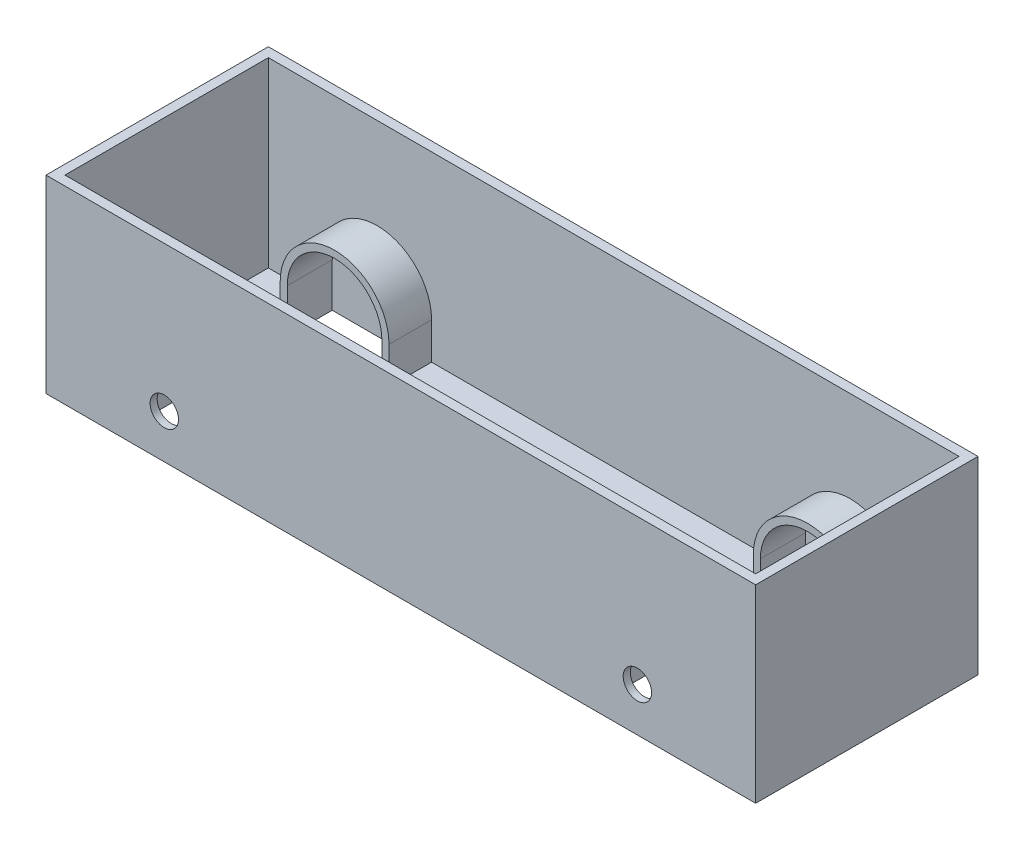
SolidWorks part; units mm, degrees
material "Aleación 1060"
ref_plane "Alzado" through (0, 0, 0) normal (0, 0, 1) x (1, 0, 0)
ref_plane "Planta" through (0, 0, 0) normal (0, 1, 0) x (1, 0, 0)
ref_plane "Vista lateral" through (0, 0, 0) normal (1, 0, 0) x (0, 0, -1)
sketch "Croquis1" plane through (0, 0, 0) normal (0, 0, 1) x (1, 0, 0)
  line L0 (0, 0) -> (50000, 0) construction
  line L1 (-120, -974.2204) -> (-120, 49025.7796) construction
  line L2 (-80, -974.2204) -> (-80, 49025.7796) construction
  line L3 (80, -1000) -> (80, 49000) construction
  line L4 (120, -1000) -> (120, 49000) construction
  line L5 (-150, 0) -> (-120, 0)
  line L6 (-80, 18.5) -> (-80, 0)
  line L7 (80, 0) -> (80, 18.5)
  line L8 (120, 18.5) -> (120, 0)
  line L9 (120, 0) -> (150, 0)
  line L10 (-80, 0) -> (80, 0)
  line L11 (-120, 18.5) -> (-120, 0)
  line L12 (-150, 3) -> (-123, 3)
  line L13 (-123, 18.5) -> (-123, 3)
  line L14 (-77, 18.5) -> (-77, 3)
  line L15 (-77, 3) -> (77, 3)
  line L16 (77, 3) -> (77, 18.5)
  line L17 (123, 18.5) -> (123, 3)
  line L18 (123, 3) -> (150, 3)
  line L19 (-150, 0) -> (-150, 3)
  line L20 (150, 0) -> (150, 3)
  circle A0 centre (-100, 18.5) radius 18.5 construction
  circle A1 centre (100, 18.5) radius 18.5 construction
  arc A2 (-80, 18.5) -> (-120, 18.5) centre (-100, 18.5) ccw
  arc A3 (120, 18.5) -> (80, 18.5) centre (100, 18.5) ccw
  arc A4 (-77, 18.5) -> (-123, 18.5) centre (-100, 18.5) ccw
  arc A5 (123, 18.5) -> (77, 18.5) centre (100, 18.5) ccw
  point P31 (0, 0)
  dimension "D2" = 37
  dimension "D3" = 40
  dimension "D1" = 200
  dimension "D4" = 300
  dimension "D5" = 3
extrude "Saliente-Extruir1" add sketch "Croquis1" along normal mid plane 94
sketch "Croquis2" plane through (123, 0, 0) normal (1, 0, 0) x (0, 0, -1)
  line L0 (-47, 3) -> (47, 3) construction
  line L1 (-25, 3) -> (25, 3)
  line L2 (-25, 3) -> (-25, 41.5)
  line L3 (-25, 41.5) -> (25, 41.5)
  line L4 (25, 3) -> (25, 41.5)
  line L5 (-47, 41.5) -> (-25, 41.5) construction
  line L6 (25, 41.5) -> (47, 41.5) construction
  dimension "D1" = 50
extrude "Cortar-Extruir1" cut sketch "Croquis2" against normal through all
sketch "Croquis3" plane through (0, 0, 47) normal (0, 0, 1) x (1, 0, 0)
  line L0 (120, 18.5) -> (120, 0) construction
  line L1 (80, 0) -> (80, 18.5) construction
  line L2 (-120, 0) -> (-120, 18.5) construction
  line L3 (-80, 18.5) -> (-80, 0) construction
  line L4 (120, 18.5) -> (120, 0)
  line L5 (80, 0) -> (80, 18.5)
  line L6 (-120, 0) -> (-120, 18.5)
  line L7 (-80, 18.5) -> (-80, 0)
  line L8 (-120, 0) -> (-80, 0)
  line L9 (80, 0) -> (120, 0)
  arc A0 (120, 18.5) -> (80, 18.5) centre (100, 18.5) ccw construction
  arc A1 (-80, 18.5) -> (-120, 18.5) centre (-100, 18.5) ccw construction
  arc A2 (120, 18.5) -> (80, 18.5) centre (100, 18.5) ccw
  arc A3 (-80, 18.5) -> (-120, 18.5) centre (-100, 18.5) ccw
extrude "Saliente-Extruir2" add sketch "Croquis3" against normal blind 3
mirror "Simetría1" about plane through (0, 0, 0) normal (0, 0, 1) of "Saliente-Extruir2"
sketch "Croquis4" plane through (0, 0, 47) normal (0, 0, 1) x (1, 0, 0)
  line L0 (150, 3) -> (150, 80)
  line L1 (150, 80) -> (-150, 80)
  line L2 (-150, 80) -> (-150, 3)
  line L10 (-150, 0) -> (150, 0)
  line L11 (150, 0) -> (150, 3)
  line L12 (150, 3) -> (123, 3)
  line L13 (123, 3) -> (123, 18.5)
  line L14 (77, 18.5) -> (77, 3)
  line L15 (77, 3) -> (-77, 3)
  line L16 (-77, 3) -> (-77, 18.5)
  line L17 (-123, 18.5) -> (-123, 3)
  line L18 (-123, 3) -> (-150, 3)
  line L19 (-150, 3) -> (-150, 0)
  line L20 (-150, 0) -> (150, 0)
  line L21 (150, 0) -> (150, 3)
  line L22 (150, 3) -> (123, 3)
  line L23 (123, 3) -> (123, 18.5)
  line L24 (77, 18.5) -> (77, 3)
  line L25 (77, 3) -> (-77, 3)
  line L26 (-77, 3) -> (-77, 18.5)
  line L27 (-123, 18.5) -> (-123, 3)
  line L28 (-123, 3) -> (-150, 3)
  line L29 (-150, 3) -> (-150, 0)
  arc A2 (123, 18.5) -> (77, 18.5) centre (100, 18.5) ccw
  arc A3 (-77, 18.5) -> (-123, 18.5) centre (-100, 18.5) ccw
  arc A4 (123, 18.5) -> (77, 18.5) centre (100, 18.5) ccw
  arc A5 (-77, 18.5) -> (-123, 18.5) centre (-100, 18.5) ccw
  line M16 (150, 3) -> (123, 3)
  line M17 (123, 3) -> (123, 18.5)
  arc M18 (123, 18.5) -> (77, 18.5) centre (100, 18.5) ccw
  line M19 (77, 18.5) -> (77, 3)
  line M20 (77, 3) -> (-77, 3)
  line M21 (-77, 3) -> (-77, 18.5)
  arc M22 (-77, 18.5) -> (-123, 18.5) centre (-100, 18.5) ccw
  line M23 (-123, 18.5) -> (-123, 3)
  line M24 (-123, 3) -> (-150, 3)
  dimension "D2" = 80
  dimension "D1" = 0
extrude "Saliente-Extruir3" add sketch "Croquis4" against normal blind 4 contours L1 L2 L0 M24 M23 M22 M21 M20 M19 M18 M17 M16
sketch "Croquis5" plane through (0, 0, -47) normal (0, 0, -1) x (-1, 0, 0)
  line L0 (123, 3) -> (150, 3) construction
  line L1 (123, 18.5) -> (123, 3) construction
  line L2 (77, 3) -> (77, 18.5) construction
  line L3 (-77, 3) -> (77, 3) construction
  line L4 (-77, 18.5) -> (-77, 3) construction
  line L5 (-123, 3) -> (-123, 18.5) construction
  line L6 (-150, 3) -> (-123, 3) construction
  line L7 (123, 3) -> (150, 3)
  line L8 (123, 18.5) -> (123, 3)
  line L9 (77, 3) -> (77, 18.5)
  line L10 (-77, 3) -> (77, 3)
  line L11 (-77, 18.5) -> (-77, 3)
  line L12 (-123, 3) -> (-123, 18.5)
  line L13 (-150, 3) -> (-123, 3)
  line L14 (150, 3) -> (150, 80)
  line L15 (150, 80) -> (-150, 80)
  line L16 (-150, 80) -> (-150, 3)
  arc A0 (123, 18.5) -> (77, 18.5) centre (100, 18.5) ccw construction
  arc A1 (-77, 18.5) -> (-123, 18.5) centre (-100, 18.5) ccw construction
  arc A2 (123, 18.5) -> (77, 18.5) centre (100, 18.5) ccw
  arc A3 (-77, 18.5) -> (-123, 18.5) centre (-100, 18.5) ccw
extrude "Saliente-Extruir4" add sketch "Croquis5" against normal blind 4
sketch "Croquis6" plane through (150, 0, 0) normal (1, 0, 0) x (0, 0, -1)
  line L0 (-43, 80) -> (43, 80)
  line L1 (43, 80) -> (43, 3) construction
  line L2 (-43, 3) -> (43, 3) construction
  line L3 (-43, 3) -> (-43, 80) construction
  line L4 (43, 80) -> (43, 3)
  line L5 (-43, 3) -> (43, 3)
  line L6 (-43, 3) -> (-43, 80)
extrude "Saliente-Extruir5" add sketch "Croquis6" against normal blind 4
sketch "Croquis7" plane through (-150, 0, 0) normal (-1, 0, 0) x (0, 0, 1)
  line L0 (-43, 80) -> (43, 80)
  line L1 (43, 80) -> (43, 3) construction
  line L2 (43, 3) -> (-43, 3) construction
  line L3 (-43, 3) -> (-43, 80) construction
  line L4 (43, 80) -> (43, 3)
  line L5 (43, 3) -> (-43, 3)
  line L6 (-43, 3) -> (-43, 80)
extrude "Saliente-Extruir6" add sketch "Croquis7" against normal blind 4
sketch "Croquis9" plane through (0, 0, 43) normal (0, 0, -1) x (-1, 0, 0)
  line L10 (123, 3) -> (146, 3)
  line L11 (146, 3) -> (146, 80)
  line L12 (146, 80) -> (-146, 80)
  line L13 (-146, 80) -> (-146, 3)
  line L14 (-146, 3) -> (-123, 3)
  line L15 (-123, 3) -> (-123, 18.5)
  line L16 (-77, 18.5) -> (-77, 3)
  line L17 (-77, 3) -> (77, 3)
  line L18 (77, 3) -> (77, 18.5)
  line L19 (123, 18.5) -> (123, 3)
  line L21 (146, 3) -> (146, 80)
  line L22 (-131.1164, 80) -> (-146, 80)
  circle A0 centre (-100, 18.5) radius 6
  circle A1 centre (100, 18.5) radius 6
  arc A2 (-77, 18.5) -> (-123, 18.5) centre (-100, 18.5) ccw
  arc A3 (123, 18.5) -> (77, 18.5) centre (100, 18.5) ccw
  dimension "D2" = 12
  dimension "D3" = 12
  dimension "D1" = 0
extrude "Cortar-Extruir2" cut sketch "Croquis9" against normal through all both and the other way through all contours A1 | A0
